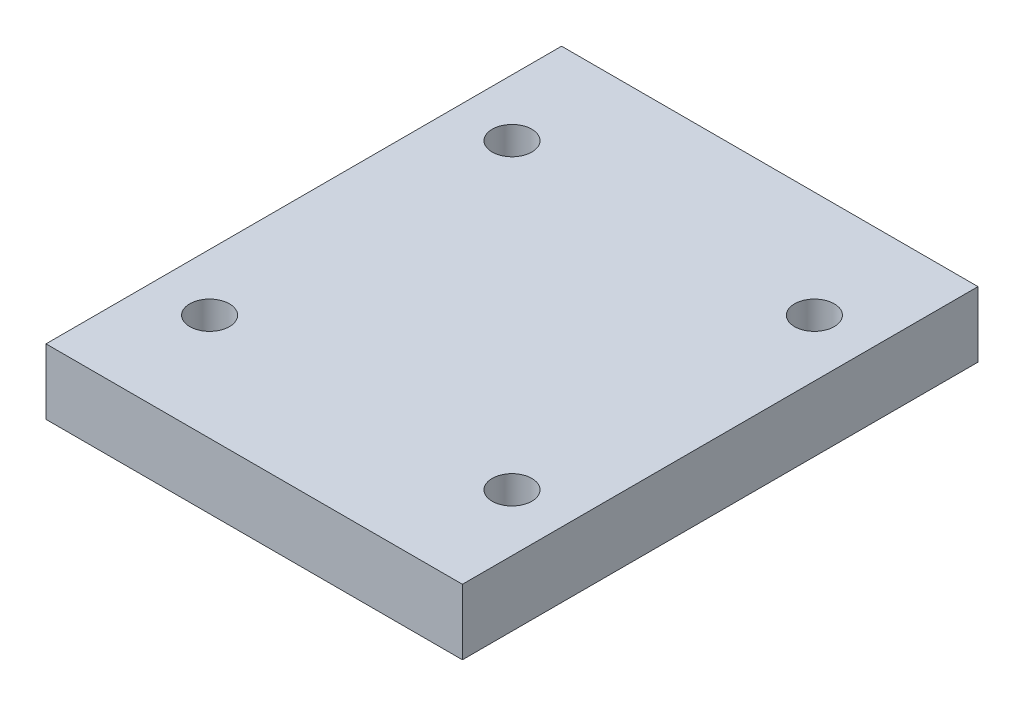
SolidWorks part; units mm, degrees
ref_plane "Front Plane" through (0, 0, 0) normal (0, 0, 1) x (1, 0, 0)
ref_plane "Top Plane" through (0, 0, 0) normal (0, 1, 0) x (1, 0, 0)
ref_plane "Right Plane" through (0, 0, 0) normal (1, 0, 0) x (0, 0, -1)
sketch "Sketch1" plane through (0, 0, 0) normal (0, 1, 0) x (1, 0, 0)
  line L1 (21, -26) -> (-21, -26)
  line L2 (21, -26) -> (21, 26)
  line L3 (21, 26) -> (-21, 26)
  line L4 (-21, -26) -> (-21, 26)
  line L5 (21, -26) -> (-21, 26) construction
  line L6 (21, 26) -> (-21, -26) construction
  point P0 (0, 0)
  dimension "D1" = 42
  dimension "D2" = 52
extrude "Boss-Extrude1" add sketch "Sketch1" along normal blind 6.6
sketch "Sketch2" plane through (0, 6.6, 0) normal (0, 1, 0) x (1, 0, 0)
  line L1 (-15.25, -15.25) -> (15.25, -15.25)
  line L2 (-15.25, -15.25) -> (-15.25, 15.25)
  line L3 (-15.25, 15.25) -> (15.25, 15.25)
  line L4 (15.25, -15.25) -> (15.25, 15.25)
  line L5 (-15.25, -15.25) -> (15.25, 15.25) construction
  line L6 (-15.25, 15.25) -> (15.25, -15.25) construction
  circle A0 centre (-15.25, 15.25) radius 2
  circle A1 centre (15.25, 15.25) radius 2
  circle A2 centre (15.25, -15.25) radius 2
  circle A3 centre (-15.25, -15.25) radius 2
  point P0 (0, 0)
  dimension "D3" = 4
  dimension "D4" = 4
  dimension "D5" = 4
  dimension "D6" = 4
  dimension "D1" = 30.5
  dimension "D2" = 30.5
extrude "Cut-Extrude2" cut sketch "Sketch2" against normal blind 6.6 contours A0 | A1 | A2 | A3
